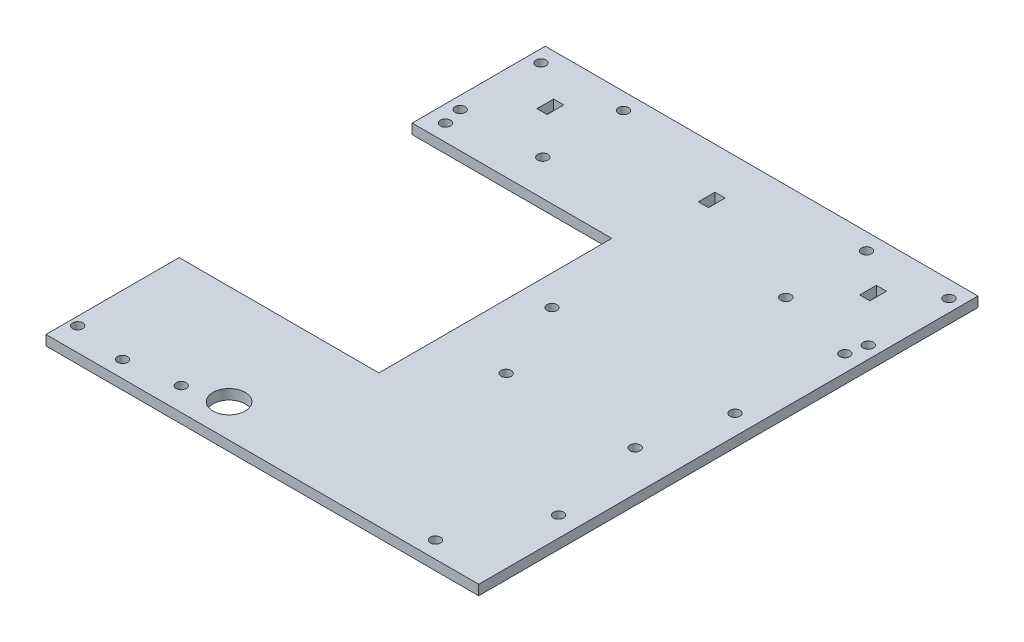
SolidWorks part; units mm, degrees
ref_plane "Front Plane" through (0, 0, 0) normal (0, 0, 1) x (1, 0, 0)
ref_plane "Top Plane" through (0, 0, 0) normal (0, 1, 0) x (1, 0, 0)
ref_plane "Right Plane" through (0, 0, 0) normal (1, 0, 0) x (0, 0, -1)
sketch "Sketch1" plane through (0, 0, 0) normal (0, 1, 0) x (1, 0, 0)
  line L0 (0, 0) -> (0, 102.7967) construction
  line L1 (-65, -75) -> (65, -75)
  line L2 (-65, -75) -> (-65, -52.5)
  line L3 (-65, 75) -> (65, 75)
  line L4 (65, -75) -> (65, -52.5)
  line L5 (-65, -75) -> (65, 75) construction
  line L6 (-65, 75) -> (65, -75) construction
  line L7 (-65, 35) -> (-5, 35)
  line L8 (-5, 35) -> (-5, -35)
  line L9 (-5, -35) -> (-65, -35)
  line L10 (-65, 35) -> (-65, 75)
  line L17 (-65, -47.5) -> (-65, -35)
  line L18 (65, -47.5) -> (65, 75)
  line L19 (46.95, 62.5) -> (46.95, 57.5)
  line L20 (-50, 62.5) -> (-46.95, 62.5)
  line L21 (-50, 62.5) -> (-50, 57.5)
  line L22 (-50, 57.5) -> (-46.95, 57.5)
  line L23 (-46.95, 62.5) -> (-46.95, 57.5)
  line L24 (50, 57.5) -> (46.95, 57.5)
  line L25 (50, 62.5) -> (50, 57.5)
  line L26 (50, 62.5) -> (46.95, 62.5)
  line L27 (65, -47.5) -> (65, -52.5)
  line L28 (-65, -52.5) -> (-65, -47.5)
  line L30 (-1.525, 57.5) -> (1.525, 57.5)
  line L31 (-1.525, 57.5) -> (-1.525, 62.5)
  line L32 (-1.525, 62.5) -> (1.525, 62.5)
  line L33 (1.525, 57.5) -> (1.525, 62.5)
  line L34 (-1.525, 57.5) -> (1.525, 62.5) construction
  line L35 (-1.525, 62.5) -> (1.525, 57.5) construction
  circle A0 centre (-61.3, 70) radius 1.525
  circle A1 centre (-61.3, 45.74) radius 1.525
  circle A2 centre (-36.5, 70) radius 1.525
  circle A3 centre (-36.5, 45.74) radius 1.525
  circle A4 centre (36.5, 45.74) radius 1.525
  circle A5 centre (36.5, 70) radius 1.525
  circle A6 centre (61.3, 45.74) radius 1.525
  circle A7 centre (61.3, 70) radius 1.525
  circle A8 centre (-47, -70) radius 1.525
  circle A9 centre (47, -70) radius 1.525
  circle A10 centre (-60, 40) radius 1.525
  circle A11 centre (60, 40) radius 1.525
  circle A12 centre (59, -45) radius 1.525
  circle A13 centre (4, 8) radius 1.525
  circle A14 centre (59, 8) radius 1.525
  circle A15 centre (53, -16) radius 1.525
  circle A16 centre (14.24, -16) radius 1.525
  circle A17 centre (-62.5, -68) radius 1.525
  circle A18 centre (-31.37, -68) radius 1.525
  circle A19 centre (-20, -65) radius 4.85
  point P0 (0, 0)
  point P50 (0, 60)
  dimension "D3" = 3.05
  dimension "D23" = 9.7
  dimension "D25" = 45
  dimension "D1" = 130
  dimension "D2" = 150
  dimension "D4" = 3.7
  dimension "D5" = 24.26
  dimension "D6" = 5
  dimension "D7" = 24.26
  dimension "D8" = 24.8
  dimension "D9" = 40
  dimension "D10" = 70
  dimension "D11" = 60
  dimension "D12" = 5
  dimension "D13" = 18
  dimension "D14" = 35
  dimension "D15" = 5
  dimension "D16" = 6
  dimension "D17" = 30
  dimension "D18" = 83
  dimension "D19" = 61
  dimension "D20" = 59
  dimension "D21" = 38.76
  dimension "D22" = 12
  dimension "D24" = 10
  dimension "D26" = 3.05
  dimension "D27" = 5
  dimension "D28" = 15
  dimension "D29" = 12.5
  dimension "D30" = 2.5
  dimension "D31" = 7
  dimension "D32" = 33.63
  dimension "D33" = 3.05
  dimension "D34" = 5
extrude "Boss-Extrude1" add sketch "Sketch1" along normal blind 3 contours L1 L4 L3 L2 A6 A4 A3 A2 A1 A0 A5 A7
